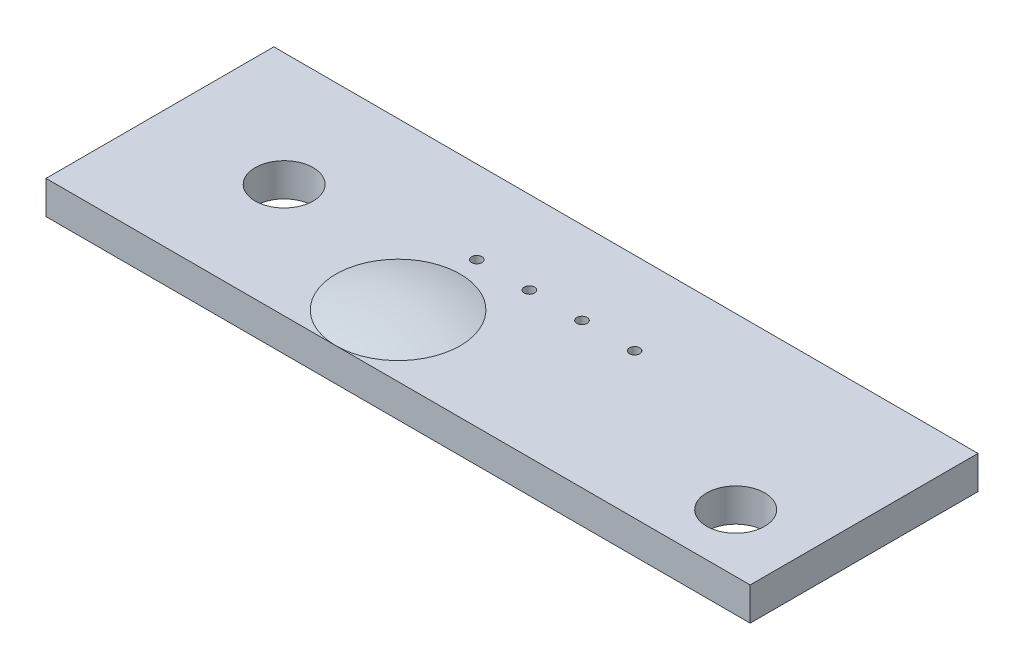
SolidWorks part; units mm, degrees
ref_plane "前视基准面" through (0, 0, 0) normal (0, 0, 1) x (1, 0, 0)
ref_plane "上视基准面" through (0, 0, 0) normal (0, 1, 0) x (1, 0, 0)
ref_plane "右视基准面" through (0, 0, 0) normal (1, 0, 0) x (0, 0, -1)
sketch "草图1" plane through (0, 0, 0) normal (0, 1, 0) x (1, 0, 0)
  line L0 (0, 13.5379) -> (0, -12.5927) construction
  line L1 (-17, 5.5) -> (17, 5.5)
  line L2 (-17, 5.5) -> (-17, -5.5)
  line L3 (-17, -5.5) -> (17, -5.5)
  line L4 (17, 5.5) -> (17, -5.5)
  line L5 (-22.1142, 0) -> (26.974, 0) construction
  dimension "D1" = 34
  dimension "D2" = 11
extrude "拉伸1" add sketch "草图1" along normal blind 1.6
sketch "草图2" plane through (0, 0, 0) normal (0, 1, 0) x (1, 0, 0)
  line L0 (-23.9258, 0) -> (21.2732, 0) construction
  line L1 (-17, 5.5) -> (-17, -5.5) construction
  line L2 (17, -5.5) -> (17, 5.5) construction
  line L3 (-17, -5.5) -> (17, -5.5) construction
  circle A0 centre (-11, 0) radius 1.4
  circle A1 centre (13.5, -2.7) radius 1.4
  dimension "D2" = 2.8
  dimension "D3" = 2.8
  dimension "D1" = 6
  dimension "D4" = 3.5
  dimension "D5" = 2.8
extrude "切除-拉伸2" cut sketch "草图2" along normal blind 6.6
ref_plane "基准面1" through (0, 0, 2.5) normal (0, 0, 1) x (1, 0, 0)
sketch "草图3" plane through (0, 0, 2.5) normal (0, 0, 1) x (1, 0, 0)
  line L0 (-3, 10.0729) -> (-3, -6.8729) construction
  line L1 (-17, 1.6) -> (-17, 0) construction
  line L3 (-17, 1.6) -> (17, 1.6) construction
  line L4 (0, 1.6) -> (-3, 1.6)
  line L5 (-3, 1.6) -> (-3, 2.0606)
  line L6 (17, 1.6) -> (-17, 1.6) construction
  arc A0 (-3, 2.0606) -> (0, 1.6) centre (-3, -7.9394) cw
  dimension "D2" = 10
  dimension "D1" = 14
  dimension "D3" = 3
revolve "旋转1" add sketch "草图3" angle 360 about L0
sketch "草图4" plane through (0, 1.6, 0) normal (0, 1, 0) x (-1, 0, 0)
  line L0 (18.3588, -1.5) -> (-17.877, -1.5) construction
  line L2 (-17, -5.5) -> (17, -5.5) construction
  line L3 (17, -5.5) -> (17, 5.5) construction
  circle A0 centre (3.2, -1.5) radius 0.25
  circle A1 centre (0.66, -1.5) radius 0.25
  circle A2 centre (-1.88, -1.5) radius 0.25
  circle A3 centre (-4.42, -1.5) radius 0.25
  dimension "D3" = 0.5
  dimension "D1" = 4
  dimension "D2" = 13.8
extrude "切除-拉伸3" cut sketch "草图4" against normal blind 10
